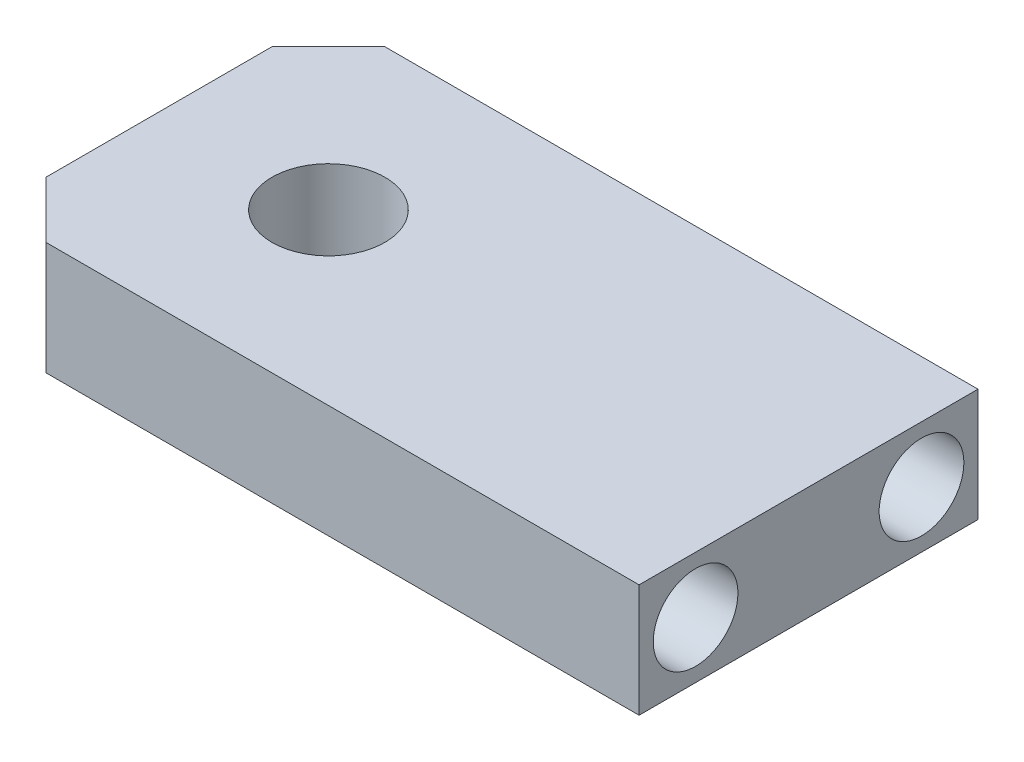
SolidWorks part; units mm, degrees
ref_plane "Front Plane" through (0, 0, 0) normal (0, 0, 1) x (1, 0, 0)
ref_plane "Top Plane" through (0, 0, 0) normal (0, 1, 0) x (1, 0, 0)
ref_plane "Right Plane" through (0, 0, 0) normal (1, 0, 0) x (0, 0, -1)
sketch "Sketch1" plane through (0, 0, 0) normal (0, 1, 0) x (1, 0, 0)
  line L1 (-11.5, 6) -> (11.5, 6)
  line L2 (-11.5, 6) -> (-11.5, -6)
  line L3 (-11.5, -6) -> (11.5, -6)
  line L4 (11.5, 6) -> (11.5, -6)
  line L5 (-11.5, 6) -> (11.5, -6) construction
  line L6 (-11.5, -6) -> (11.5, 6) construction
  point P0 (0, 0)
  dimension "D1" = 23
  dimension "D2" = 12
extrude "Boss-Extrude1" add sketch "Sketch1" along normal blind 4
sketch "Sketch2" plane through (11.5, 0, 0) normal (1, 0, 0) x (0, 0, -1)
  line L0 (6, 4) -> (6, 0) construction
  line L1 (-6, 4) -> (-6, 0) construction
  circle A0 centre (-4, 2) radius 1.5
  circle A1 centre (4, 2) radius 1.5
  point P6 (0, 0)
  point P9 (-6, 2)
  dimension "D1" = 3
  dimension "D2" = 3
  dimension "D3" = 2
  dimension "D4" = 2
extrude "Cut-Extrude1" cut sketch "Sketch2" against normal blind 10
sketch "Sketch3" plane through (0, 4, 0) normal (0, 1, 0) x (1, 0, 0)
  line L0 (11.5, -6) -> (11.5, 6) construction
  circle A0 centre (-5.5, 0) radius 2
  point P4 (0, 0)
  dimension "D1" = 4
  dimension "D2" = 17
extrude "Cut-Extrude2" cut sketch "Sketch3" against normal through all
chamfer "Chamfer1" distance 2 angle 45 2 edges at (-11.5, 2, 6) (-11.5, 2, -6)
